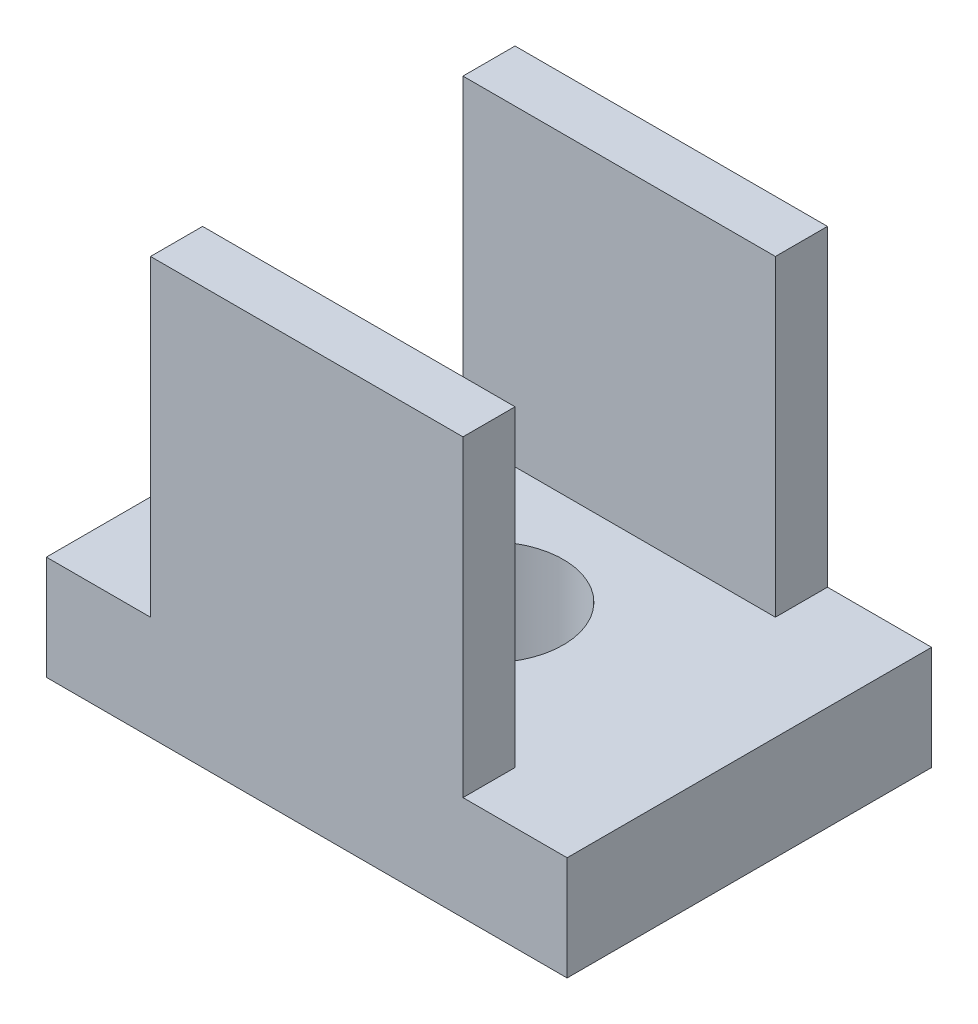
SolidWorks part; units mm, degrees
ref_plane "Front Plane" through (0, 0, 0) normal (0, 0, 1) x (1, 0, 0)
ref_plane "Top Plane" through (0, 0, 0) normal (0, 1, 0) x (1, 0, 0)
ref_plane "Right Plane" through (0, 0, 0) normal (1, 0, 0) x (0, 0, -1)
sketch "Sketch1" plane through (0, 0, 0) normal (0, 1, 0) x (1, 0, 0)
  line L1 (-5, -3.5) -> (5, -3.5)
  line L2 (-5, -3.5) -> (-5, 3.5)
  line L3 (-5, 3.5) -> (5, 3.5)
  line L4 (5, -3.5) -> (5, 3.5)
  line L5 (-5, -3.5) -> (5, 3.5) construction
  line L6 (-5, 3.5) -> (5, -3.5) construction
  circle A0 centre (0, 0) radius 1.425
  point P0 (0, 0)
  dimension "D3" = 2.85
  dimension "D1" = 10
  dimension "D2" = 7
extrude "Boss-Extrude1" add sketch "Sketch1" along normal blind 2 contours L3 L4 L1 L2 | A0
sketch "Sketch2" plane through (0, 2, 0) normal (0, 1, 0) x (1, 0, 0)
  line L0 (-5, 0) -> (5, 0) construction
  line L1 (-5, -3.5) -> (-5, 3.5) construction
  line L2 (5, -3.5) -> (5, 3.5) construction
  line L3 (0, 3.5) -> (0, -3.5) construction
  line L4 (-5, 3.5) -> (5, 3.5) construction
  line L5 (-5, -3.5) -> (5, -3.5) construction
  line L6 (-3, -3.5) -> (3, -3.5)
  line L7 (-3, 2.5) -> (3, 2.5)
  line L8 (-3, 2.5) -> (-3, 3.5)
  line L9 (-3, 3.5) -> (3, 3.5)
  line L10 (3, 2.5) -> (3, 3.5)
  line L11 (3, -2.5) -> (3, -3.5)
  line L12 (-3, -2.5) -> (3, -2.5)
  line L13 (-3, -2.5) -> (-3, -3.5)
  dimension "D1" = 6
  dimension "D2" = 1
  dimension "D3" = 2
extrude "Boss-Extrude2" add sketch "Sketch2" along normal blind 6
